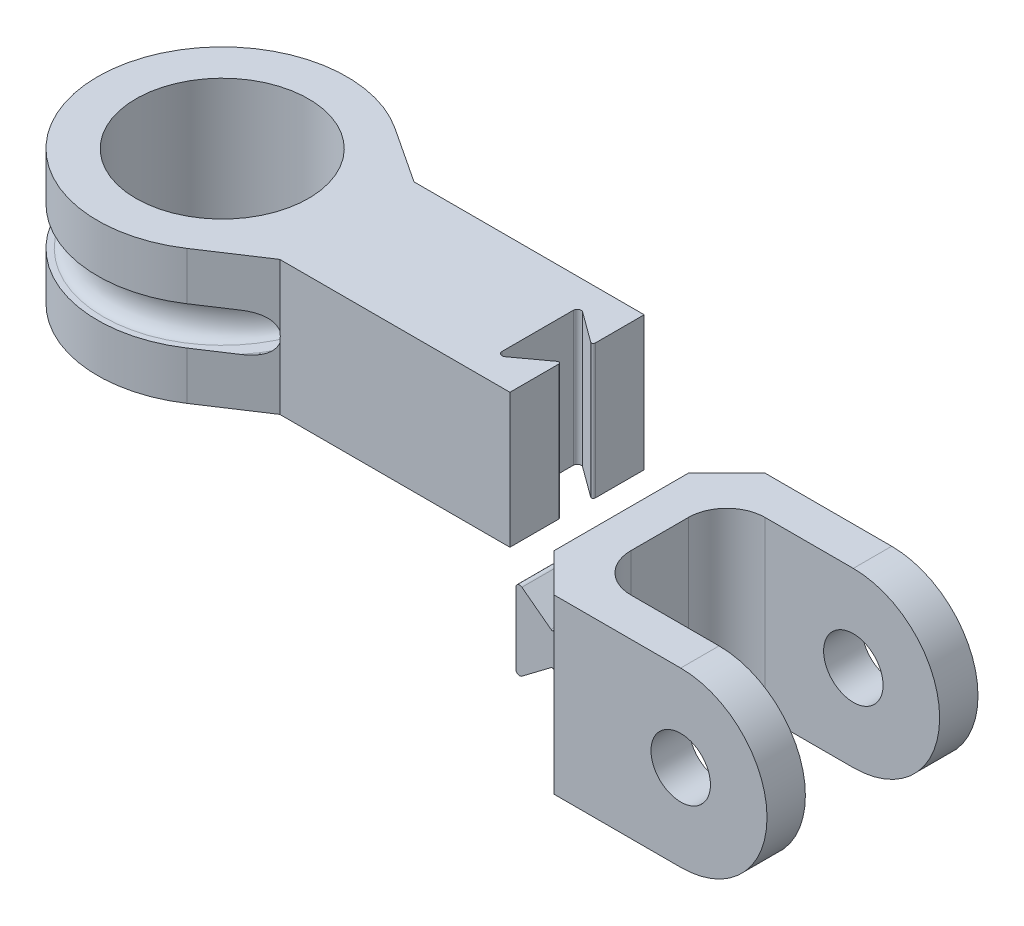
SolidWorks part; units mm, degrees
ref_plane "Front Plane" through (0, 0, 0) normal (0, 0, 1) x (1, 0, 0)
ref_plane "Top Plane" through (0, 0, 0) normal (0, 1, 0) x (1, 0, 0)
ref_plane "Right Plane" through (0, 0, 0) normal (1, 0, 0) x (0, 0, -1)
sketch "Sketch2" plane through (0, 0, 0) normal (0, 1, 0) x (1, 0, 0)
  line L0 (-31.5521, 0) -> (4.1182, 0) construction
  line L1 (0, -16.8489) -> (0, 18.0055) construction
  line L2 (-5.8318, 3.5) -> (-8.7538, 5.4266)
  line L3 (-5.8318, -3.5) -> (6.1682, -3.5)
  line L5 (-5.8318, 3.5) -> (6.1682, 3.5)
  line L6 (6.1682, -3.5) -> (6.1682, -0.9521)
  line L7 (-5.8318, -3.5) -> (6.1682, 3.5) construction
  line L8 (-5.8318, 3.5) -> (6.1682, -3.5) construction
  line L14 (4.1182, -1.8608) -> (4.1182, 1.8608)
  line L17 (-5.8318, -3.5) -> (-8.7538, -5.4266)
  line L18 (-5.8318, -3.5) -> (-5.8318, 3.5) construction
  line L19 (6.1682, -2.255) -> (6.1682, -0.9521)
  line L20 (6.0091, 0.8714) -> (4.4363, 2.0222)
  line L21 (6.0091, -0.8714) -> (4.4363, -2.0222)
  line L22 (6.1682, 0.9521) -> (6.1682, 3.5)
  line L23 (-12.3318, 8.2204) -> (-12.3318, -9.087) construction
  arc A0 (-8.7538, 5.4266) -> (-8.7538, -5.4266) centre (-12.3318, 0) ccw
  circle A1 centre (-12.3318, 0) radius 4.5
  arc A2 (4.1182, 1.8608) -> (4.4363, 2.0222) centre (4.3182, 1.8608) cw
  arc A3 (4.4363, -2.0222) -> (4.1182, -1.8608) centre (4.3182, -1.8608) cw
  arc A4 (6.0091, 0.8714) -> (6.1682, 0.9521) centre (6.0682, 0.9521) ccw
  arc A5 (6.1682, -0.9521) -> (6.0091, -0.8714) centre (6.0682, -0.9521) ccw
  point P5 (0.1682, 0)
  point P13 (6.1682, 0)
  point P14 (6.1682, 0)
  point P23 (0, 0)
  point P29 (6.1682, 0.755)
  point P30 (-12.3318, 0)
  dimension "D3" = 13
  dimension "D4" = 9
  dimension "D5" = 0.2
  dimension "D6" = 0.2
  dimension "D7" = 0.1
  dimension "D8" = 0.1
  dimension "D1" = 12
  dimension "D2" = 7
sketch "Sketch3" plane through (0, 0, 0) normal (0, 0, 1) x (1, 0, 0)
  line L0 (0, 0) -> (11.3825, 0) construction
  line L2 (9.9727, -1.8484) -> (9.9727, 1.8484)
  line L5 (10.1528, -2.0474) -> (11.3825, 0) construction
  line L6 (10.1528, 2.0474) -> (11.3825, 0) construction
  line L10 (11.8124, -0.861) -> (10.2932, -2.008)
  line L11 (11.8124, 0.861) -> (10.2932, 2.008)
  line L12 (11.3825, 0) -> (20.5128, 0) construction
  line L18 (11.9727, 0.9408) -> (11.9727, 4.5)
  line L19 (13.9727, -4.5) -> (11.9727, -4.5)
  line L21 (13.9727, -4.5) -> (13.9727, 4.5)
  line L22 (13.9727, 4.5) -> (11.9727, 4.5)
  line L23 (11.9727, -4.5) -> (11.9727, -0.9408)
  line L24 (13.9727, -4.5) -> (11.9727, 4.5) construction
  line L25 (13.9727, 4.5) -> (11.9727, -4.5) construction
  arc A0 (9.9727, 1.8484) -> (10.2932, 2.008) centre (10.1727, 1.8484) cw
  arc A1 (10.2932, -2.008) -> (9.9727, -1.8484) centre (10.1727, -1.8484) cw
  arc A2 (11.9727, -0.9408) -> (11.8124, -0.861) centre (11.8727, -0.9408) ccw
  arc A3 (11.9727, 0.9408) -> (11.8124, 0.861) centre (11.8727, 0.9408) cw
  point P0 (11.3825, 0)
  point P1 (12.609, 0)
  point P4 (9.9727, 0)
  point P10 (12.9727, 0)
  point P20 (11.3825, -0.74)
  point P23 (11.3825, 0.74)
  dimension "D4" = 0.2
  dimension "D5" = 0.1
  dimension "D1" = 2
  dimension "D2" = 9
extrude "Boss-Extrude3" add sketch "Sketch2" along normal blind 7 contours L6 A5 L21 A3 L14 A2 L20 A4 L22 L5 L2 A0 L17 L3 A1
ref_plane "Plane4" through (-12.33, 0, 0) normal (1, 0, 0) x (0, 0, -1)
sketch "Sketch19" plane through (-12.33, -4.4652, -12.7936) normal (1, 0, 0) x (0, 1, 0)
  line L0 (6.9652, 6.5986) -> (6.9652, 5.9886)
  line L1 (8.9652, 5.9886) -> (8.9652, 6.5986)
  line L4 (11.4652, 6.2936) -> (4.4652, 6.2936) construction
  line L5 (11.4652, 12.7936) -> (4.4652, 12.7936) construction
  line L7 (11.4652, 6.2936) -> (11.4652, 19.2936) construction
  ellipse E0 centre (7.9652, 5.9886) end of major axis (8.9652, 5.9886) minor radius 0.6 (6.9652, 5.9886) -> (8.9652, 5.9886) ccw
  ellipse E1 centre (7.9652, 6.5986) end of major axis (6.9652, 6.5986) minor radius 0.6 (6.9652, 6.5986) -> (8.9652, 6.5986) cw
  point P16 (6.9652, 6.2936)
  dimension "D1" = 1.81
  dimension "D2" = 2.5
revolve "Cut-Revolve1" cut sketch "Sketch19" angle 360 about L5
extrude "Boss-Extrude4" add sketch "Sketch3" along normal blind 7 contours A2 L10 A1 L2 A0 L11 A3 L18 L22 L21 L19 L23
sketch "Sketch15" plane through (0, 0, 7) normal (0, 0, 1) x (1, 0, 0)
  line L1 (11.9727, 4.5) -> (20.5727, 4.5)
  line L2 (11.9727, 4.5) -> (11.9727, -4.5)
  line L3 (11.9727, -4.5) -> (20.5727, -4.5)
  arc A0 (20.5727, -4.5) -> (20.5727, 4.5) centre (20.5727, 0) ccw
  dimension "D3" = 9
extrude "Boss-Extrude10" add sketch "Sketch15" along normal blind 2
sketch "Sketch16" plane through (0, 4.5, 0) normal (0, 1, 0) x (1, 0, 0)
  line L0 (13.9727, -7) -> (13.9727, -11.2162) construction
  line L1 (11.9727, -7) -> (13.9727, -7) construction
  line L2 (20.5727, -9) -> (11.9727, -9) construction
  line L3 (11.9727, -9) -> (11.9727, 0) construction
  line L4 (11.9727, -7) -> (13.9727, -9)
  line L5 (11.9727, -7) -> (11.9727, -9)
  line L6 (11.9727, -9) -> (13.9727, -9)
  point P4 (13.9727, -9)
  point P6 (11.9727, -7)
extrude "Cut-Extrude6" cut sketch "Sketch16" against normal through all contours L6 L4 L5
fillet "Fillet4" radius 2 1 edges at (13.9727, 0, 7)
sketch "Sketch18" plane through (0, 0, 9) normal (0, 0, 1) x (1, 0, 0)
  line L0 (13.9727, 0) -> (30.274, 0) construction
  line L1 (13.9727, -4.5) -> (13.9727, 4.5) construction
  line L2 (25.0727, 0) -> (20.5727, 0) construction
  circle A0 centre (20.5727, 0) radius 1.55
  arc A1 (20.5727, -4.5) -> (20.5727, 4.5) centre (20.5727, 0) ccw construction
  dimension "D1" = 3.1
  dimension "D2" = 4.5
extrude "Cut-Extrude7" cut sketch "Sketch18" against normal blind 2 contours A0
ref_plane "Plane3" through (0, 0, 3.5) normal (0, 0, 1) x (1, 0, 0)
mirror "Mirror7" about plane through (0, 0, 3.5) normal (0, 0, 1) of "Boss-Extrude10", "Cut-Extrude6", "Cut-Extrude7"
fillet "Fillet6" radius 2 1 edges at (13.9727, 0, 0)
